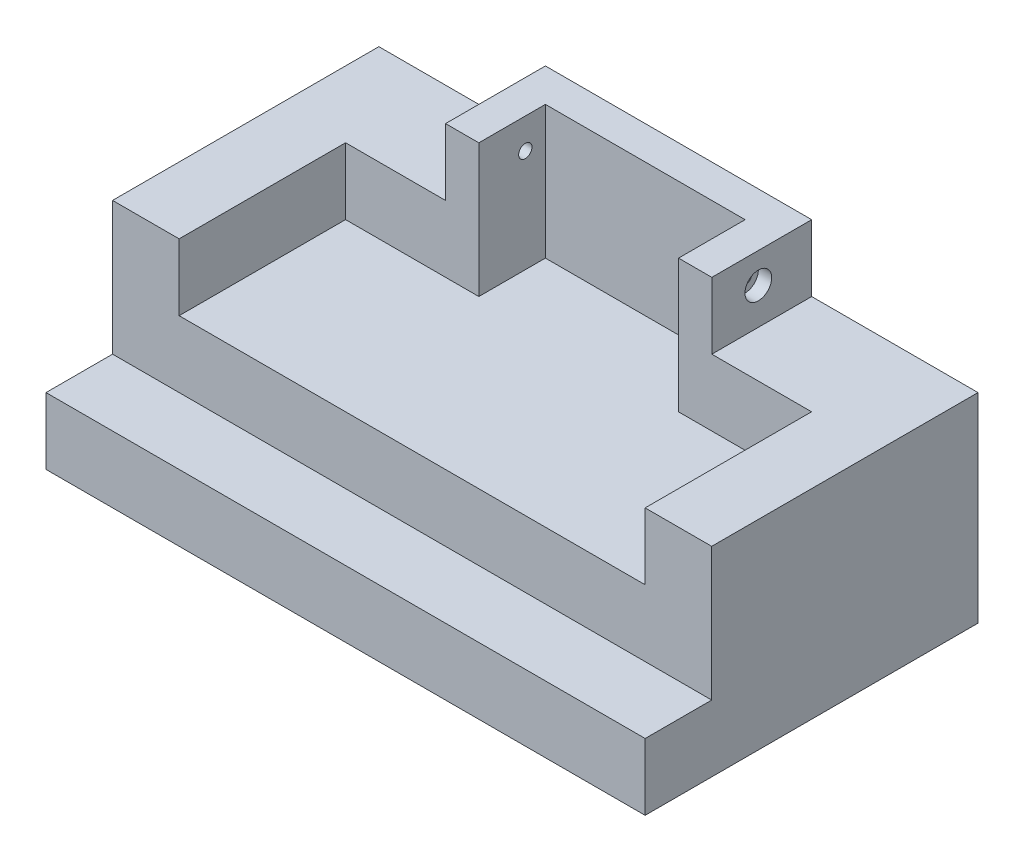
SolidWorks part; units mm, degrees
ref_plane "Front Plane" through (0, 0, 0) normal (0, 0, 1) x (1, 0, 0)
ref_plane "Top Plane" through (0, 0, 0) normal (0, 1, 0) x (1, 0, 0)
ref_plane "Right Plane" through (0, 0, 0) normal (1, 0, 0) x (0, 0, -1)
sketch "Sketch2" plane through (0, 0, 0) normal (0, 1, 0) x (1, 0, 0)
  line L1 (0, 0) -> (4.5, 0)
  line L2 (0, 0) -> (0, 2.5)
  line L3 (0, 2.5) -> (4.5, 2.5)
  line L4 (4.5, 0) -> (4.5, 2.5)
  dimension "D1" = 4.5
  dimension "D2" = 2.5
extrude "Boss-Extrude1" add sketch "Sketch2" along normal blind 2
sketch "Sketch6" plane through (0, 2, 0) normal (0, 1, 0) x (1, 0, 0)
  line L1 (4.5, 2.5) -> (0, 2.5) construction
  line L4 (1.5009, 2.25) -> (1.5009, 1.75)
  line L5 (3.0009, 2.25) -> (3.0009, 1.75)
  line L6 (1.2509, 2.5) -> (1.2509, 1.75)
  line L7 (3.2509, 2.5) -> (3.2509, 1.75)
  line L10 (1.2509, 1.75) -> (1.5009, 1.75)
  line L11 (1.2509, 2.5) -> (3.2509, 2.5)
  line L12 (0, 2.5) -> (0, 0) construction
  line L13 (3.0009, 1.75) -> (3.2509, 1.75)
  line L15 (1.5009, 2.25) -> (3.0009, 2.25)
  dimension "D1" = 1.2509
  dimension "D2" = 0.25
  dimension "D3" = 0.25
  dimension "D4" = 2
  dimension "D5" = 0.75
  dimension "D6" = 0.75
  dimension "D7" = 0.5
extrude "Cut-Extrude3" cut sketch "Sketch6" against normal blind 0.5
sketch "Sketch9" plane through (0, 1.5, 0) normal (0, 1, 0) x (1, 0, 0)
  line L1 (0.5, 1.75) -> (0.5, 0.4999)
  line L3 (4, 1.75) -> (4, 0.4999)
  line L4 (0, 2.5) -> (0, 0) construction
  line L5 (4.5, 0) -> (4.5, 2.5) construction
  line L6 (0.5, 0.4999) -> (4, 0.4999)
  line L9 (0.5, 1.75) -> (4, 1.75)
  line L10 (4.5, 2.5) -> (3.2509, 2.5) construction
  line L11 (0, 0) -> (4.5, 0) construction
  dimension "D1" = 0.5
  dimension "D2" = 0.5
  dimension "D3" = 0.75
  dimension "D4" = 0.4999
extrude "Cut-Extrude5" cut sketch "Sketch9" against normal blind 0.5
sketch "Sketch10" plane through (0, 1.5, 0) normal (0, 1, 0) x (1, 0, 0)
  line L0 (0.5, 0.4999) -> (0, 0.4999)
  line L1 (0, 2.5) -> (0, 0) construction
  line L2 (0, 0.4999) -> (0, 0)
  line L3 (0, 0) -> (4.5, 0)
  line L4 (4.5, 0) -> (4.5, 0.4999)
  line L5 (4.5, 0) -> (4.5, 2.5) construction
  line L6 (4.5, 0.4999) -> (0.5, 0.4999)
extrude "Cut-Extrude6" cut sketch "Sketch10" against normal blind 1
hole_wizard "CBORE for M2 Hex Head Machine Screw1" positions "Sketch14" profile "Sketch16" counterbore size "M2" standard "ANSI Metric"
sketch "Sketch14" plane through (3.2509, 0, 0) normal (1, 0, 0) x (0, 0, -1)
  point P0 (2.0993, 1.7728)
sketch "Sketch16" plane through (3.2509, 1.7728, -2.0993) normal (0, 1, 0) x (0, 0, -1)
  line L0 (0, 0) -> (0, 2.03)
  line L1 (0, 2.03) -> (0.05, 2)
  line L2 (0.05, 2) -> (0.05, 0.1)
  line L3 (0.05, 0.1) -> (0.1, 0.1)
  line L4 (0.1, 0.1) -> (0.1, 0)
  line L5 (0.1, 0) -> (0, 0)
  line L10 (0, 2.03) -> (-0.05, 2) construction
  line L11 (0, -6.35) -> (0, 107.95) construction
  dimension "Hole Dia." = 0.1
  dimension "Hole Depth" = 2
  dimension "C'Bore Dia." = 0.2
  dimension "C'Bore Depth" = 0.1
  dimension "Drill Angle" = 118
